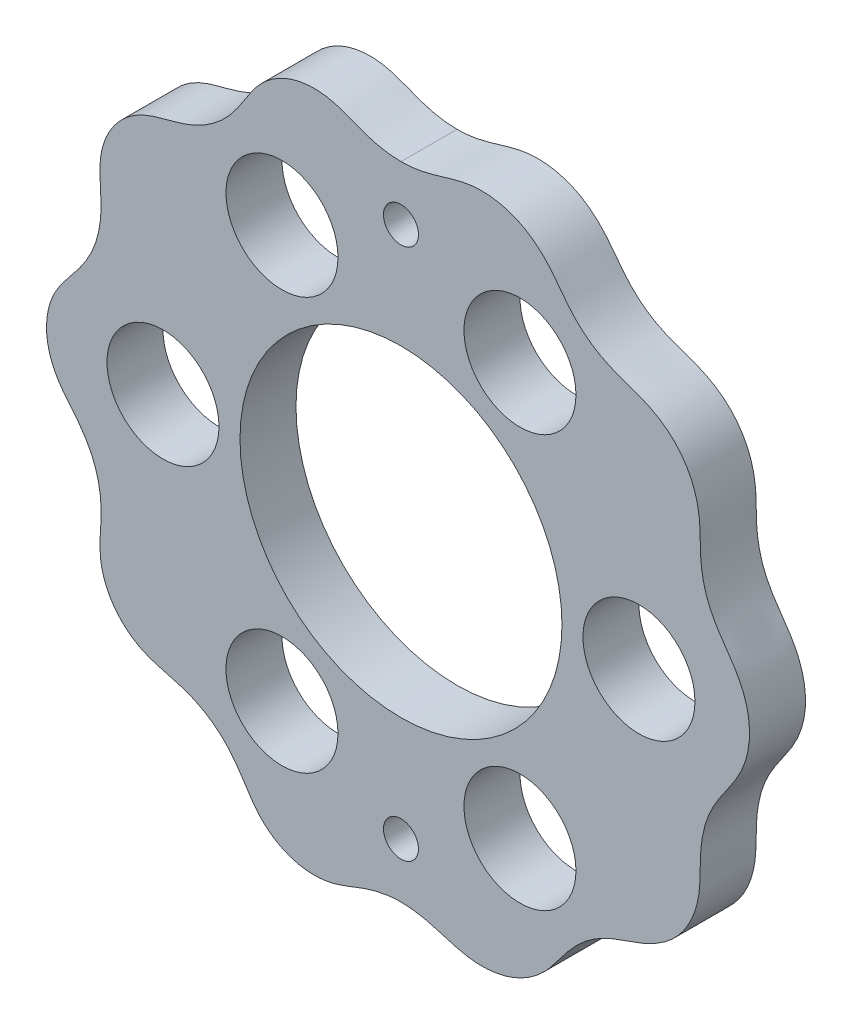
SolidWorks part; units mm, degrees
ref_plane "Front Plane" through (0, 0, 0) normal (1, 0, 0) x (0, 1, 0)
ref_plane "Top Plane" through (0, 0, 0) normal (0, 0, 1) x (0, 1, 0)
ref_plane "Right Plane" through (0, 0, 0) normal (0, 1, 0) x (-1, 0, 0)
sketch "Sketch1" plane through (0, 0, 0) normal (0, 0, 1) x (0, 1, 0)
  line L1 (23, 0) -> (-23, 0) construction
  spline S0 degree 4 poles (23.9407, 7.1162) (23.9885, 6.8946) (24.0625, 6.447) (24.1082, 5.7663) (24.0486, 4.9729) (23.9249, 4.3036) (23.7849, 3.7545) (23.6576, 3.3195) (23.5234, 2.8867) (23.3915, 2.4529) (23.27, 2.0165) (23.1655, 1.5748) (23.0935, 1.1854) (23.0516, 0.8757) (23.029, 0.6506) (23.0178, 0.5112) (23.0107, 0.398) (23.0053, 0.2791) (23.0017, 0.156) (22.9998, 0.0377) (22.9999, -0.0574) (23.0024, -0.1955) (23.0078, -0.3449) (23.0177, -0.5187) (23.0349, -0.7205) (23.0624, -0.9622) (23.1037, -1.2338) (23.154, -1.505) (23.2128, -1.774) (23.3284, -2.2422) (23.4854, -2.7704) (23.6744, -3.3607) (23.8702, -4.0673) (24.0032, -4.6933) (24.1066, -5.5543) (24.081, -6.4684) (23.913, -7.3677) (23.6084, -8.2271) (23.286, -8.8817) (22.8404, -9.5702) (22.2483, -10.2641) (21.497, -10.9281) (20.6148, -11.5684) (19.6504, -12.3151) (18.7036, -13.2841) (17.9844, -14.4202) (17.4982, -15.6468) (17.1396, -16.7614) (16.7678, -17.7216) (16.2174, -18.7181) (15.4262, -19.6865) (14.3018, -20.5828) (12.8167, -21.2533) (11.3354, -21.4856) (9.9796, -21.4697) (8.5912, -21.5223) (7.381, -21.7294) (6.1993, -22.1854) (5.0909, -22.8531) (4.209, -23.4942) (3.2301, -24.158) (2.0738, -24.7085) (0.7346, -25.0284) (-0.7346, -25.0284) (-2.0738, -24.7085) (-3.2301, -24.158) (-4.209, -23.4942) (-5.0909, -22.8531) (-6.1993, -22.1854) (-7.381, -21.7294) (-8.5912, -21.5223) (-9.9796, -21.4697) (-11.3354, -21.4856) (-12.8167, -21.2533) (-14.3018, -20.5828) (-15.4262, -19.6865) (-16.2174, -18.7181) (-16.7678, -17.7216) (-17.1396, -16.7614) (-17.4982, -15.6468) (-17.9844, -14.4202) (-18.7036, -13.2841) (-19.6504, -12.3151) (-20.6148, -11.5684) (-21.497, -10.9281) (-22.2483, -10.2641) (-22.8404, -9.5702) (-23.286, -8.8817) (-23.6084, -8.2271) (-23.913, -7.3677) (-24.081, -6.4684) (-24.1066, -5.5543) (-24.0032, -4.6933) (-23.8702, -4.0672) (-23.7111, -3.4935) (-23.5485, -2.9672) (-23.4068, -2.5063) (-23.2954, -2.1084) (-23.2128, -1.774) (-23.1541, -1.505) (-23.1037, -1.2338) (-23.0624, -0.9622) (-23.0349, -0.7205) (-23.0177, -0.5187) (-23.0078, -0.3449) (-23.0024, -0.1955) (-22.9999, -0.0574) (-22.9998, 0.0377) (-23.0017, 0.156) (-23.0053, 0.2791) (-23.0107, 0.398) (-23.0178, 0.5113) (-23.029, 0.6506) (-23.0459, 0.8192) (-23.0706, 1.0168) (-23.1141, 1.2964) (-23.1786, 1.6304) (-23.27, 2.0163) (-23.3915, 2.453) (-23.5234, 2.8866) (-23.6576, 3.3195) (-23.7849, 3.7545) (-23.9249, 4.3036) (-24.0486, 4.9729) (-24.1082, 5.7663) (-24.0625, 6.447) (-23.9885, 6.8946) (-23.9407, 7.1162) knots 0 0 0 0 0 0.009712 0.019424 0.029136 0.033992 0.038848 0.043704 0.04856 0.053416 0.058272 0.063128 0.067984 0.070412 0.071626 0.07284 0.074054 0.075268 0.076483 0.077697 0.079172 0.080648 0.082124 0.0836 0.086551 0.089503 0.092455 0.095406 0.098358 0.10131 0.113116 0.119019 0.124923 0.132722 0.14052 0.156118 0.163917 0.171717 0.179516 0.187315 0.198996 0.210676 0.222357 0.234038 0.251232 0.268425 0.279434 0.290443 0.301452 0.312461 0.328059 0.343658 0.362557 0.381456 0.391612 0.401768 0.42208 0.433761 0.445442 0.457123 0.468804 0.484402 0.5 0.515598 0.531196 0.542877 0.554558 0.566239 0.57792 0.598232 0.608388 0.618544 0.637443 0.656342 0.671941 0.687539 0.698548 0.709557 0.720566 0.731575 0.748768 0.765962 0.777643 0.789324 0.801004 0.812685 0.820484 0.828283 0.836083 0.843882 0.85948 0.867278 0.875077 0.880981 0.886884 0.892787 0.89869 0.901642 0.904594 0.907545 0.910497 0.913449 0.9164 0.917876 0.919352 0.920828 0.922303 0.923517 0.924732 0.925946 0.92716 0.928374 0.929588 0.932016 0.934444 0.936872 0.941728 0.946584 0.95144 0.956296 0.961152 0.966008 0.970864 0.980576 0.990288 1 1 1 1 1 construction
  spline S1 degree 4 poles (23, 0) (23, -0.0291) (23.0004, -0.0871) (23.0024, -0.1955) (23.0078, -0.3449) (23.0177, -0.5187) (23.0349, -0.7205) (23.0624, -0.9622) (23.1037, -1.2338) (23.154, -1.505) (23.2128, -1.774) (23.3284, -2.2422) (23.4854, -2.7704) (23.6744, -3.3607) (23.8702, -4.0673) (24.0032, -4.6933) (24.1066, -5.5543) (24.081, -6.4684) (23.913, -7.3677) (23.6084, -8.2271) (23.286, -8.8817) (22.8404, -9.5702) (22.2483, -10.2641) (21.497, -10.9281) (20.6148, -11.5684) (19.6504, -12.3151) (18.7036, -13.2841) (17.9844, -14.4202) (17.4982, -15.6468) (17.1396, -16.7614) (16.7678, -17.7216) (16.2174, -18.7181) (15.4262, -19.6865) (14.3018, -20.5828) (12.8167, -21.2533) (11.3354, -21.4856) (9.9796, -21.4697) (8.5912, -21.5223) (7.381, -21.7294) (6.1993, -22.1854) (5.0909, -22.8531) (4.209, -23.4942) (3.2301, -24.158) (2.0738, -24.7085) (0.7346, -25.0284) (-0.7346, -25.0284) (-2.0738, -24.7085) (-3.2301, -24.158) (-4.209, -23.4942) (-5.0909, -22.8531) (-6.1993, -22.1854) (-7.381, -21.7294) (-8.5912, -21.5223) (-9.9796, -21.4697) (-11.3354, -21.4856) (-12.8167, -21.2533) (-14.3018, -20.5828) (-15.4262, -19.6865) (-16.2174, -18.7181) (-16.7678, -17.7216) (-17.1396, -16.7614) (-17.4982, -15.6468) (-17.9844, -14.4202) (-18.7036, -13.2841) (-19.6504, -12.3151) (-20.6148, -11.5684) (-21.497, -10.9281) (-22.2483, -10.2641) (-22.8404, -9.5702) (-23.286, -8.8817) (-23.6084, -8.2271) (-23.913, -7.3677) (-24.081, -6.4684) (-24.1066, -5.5543) (-24.0032, -4.6933) (-23.8702, -4.0672) (-23.7111, -3.4935) (-23.5485, -2.9672) (-23.4068, -2.5063) (-23.2954, -2.1084) (-23.2128, -1.774) (-23.1541, -1.505) (-23.1037, -1.2338) (-23.0624, -0.9622) (-23.0349, -0.7205) (-23.0177, -0.5187) (-23.0078, -0.3449) (-23.0024, -0.1955) (-23.0004, -0.0871) (-23, -0.0291) (-23, 0) knots 0.077697 0.077697 0.077697 0.077697 0.077697 0.079172 0.080648 0.082124 0.0836 0.086551 0.089503 0.092455 0.095406 0.098358 0.10131 0.113116 0.119019 0.124923 0.132722 0.14052 0.156118 0.163917 0.171717 0.179516 0.187315 0.198996 0.210676 0.222357 0.234038 0.251232 0.268425 0.279434 0.290443 0.301452 0.312461 0.328059 0.343658 0.362557 0.381456 0.391612 0.401768 0.42208 0.433761 0.445442 0.457123 0.468804 0.484402 0.5 0.515598 0.531196 0.542877 0.554558 0.566239 0.57792 0.598232 0.608388 0.618544 0.637443 0.656342 0.671941 0.687539 0.698548 0.709557 0.720566 0.731575 0.748768 0.765962 0.777643 0.789324 0.801004 0.812685 0.820484 0.828283 0.836083 0.843882 0.85948 0.867278 0.875077 0.880981 0.886884 0.892787 0.89869 0.901642 0.904594 0.907545 0.910497 0.913449 0.9164 0.917876 0.919352 0.920828 0.922303 0.922303 0.922303 0.922303 0.922303
  spline S2 degree 4 poles (23, 0) (23, 0.1298) (23.0072, 0.4175) (23.0429, 0.8624) (23.1413, 1.4589) (23.2955, 2.0725) (23.4927, 2.6734) (23.7201, 3.2633) (23.9562, 3.8495) (24.1887, 4.4936) (24.3725, 5.2081) (24.4884, 6.2045) (24.367, 7.4987) (23.9005, 8.7389) (23.1142, 9.8103) (22.2077, 10.6059) (21.3141, 11.1767) (20.344, 11.7778) (19.3918, 12.5544) (18.5739, 13.4856) (17.9316, 14.559) (17.5362, 15.5855) (17.292, 16.5023) (17.061, 17.4211) (16.7439, 18.4274) (16.0925, 19.5887) (15.0517, 20.5947) (13.8291, 21.2551) (12.6398, 21.5687) (11.568, 21.6347) (10.5015, 21.5515) (9.4322, 21.4941) (8.3591, 21.5578) (7.3047, 21.7772) (6.2544, 22.1732) (5.2406, 22.7553) (4.2871, 23.5015) (3.3439, 24.3298) (2.1726, 25.0453) (0.7455, 25.4647) (-0.7455, 25.4647) (-2.1726, 25.0453) (-3.3439, 24.3298) (-4.2871, 23.5015) (-5.2406, 22.7553) (-6.2544, 22.1732) (-7.3047, 21.7772) (-8.3591, 21.5578) (-9.4322, 21.4941) (-10.5015, 21.5515) (-11.568, 21.6347) (-12.6398, 21.5687) (-13.8291, 21.2551) (-15.0517, 20.5947) (-16.0925, 19.5887) (-16.7439, 18.4274) (-17.061, 17.4211) (-17.292, 16.5023) (-17.5362, 15.5855) (-17.9316, 14.559) (-18.5739, 13.4856) (-19.3918, 12.5544) (-20.344, 11.7778) (-21.3141, 11.1767) (-22.2077, 10.6059) (-23.1142, 9.8103) (-23.9005, 8.7389) (-24.367, 7.4987) (-24.4884, 6.2045) (-24.3725, 5.2081) (-24.1887, 4.4936) (-23.9562, 3.8495) (-23.7201, 3.2633) (-23.4927, 2.6734) (-23.2955, 2.0725) (-23.1413, 1.4589) (-23.0429, 0.8624) (-23.0072, 0.4175) (-23, 0.1298) (-23, 0) knots 0.117046 0.117046 0.117046 0.117046 0.117046 0.121959 0.127941 0.133924 0.139906 0.145889 0.151871 0.157854 0.163836 0.171793 0.17975 0.195664 0.212603 0.221072 0.229542 0.24112 0.252698 0.264276 0.275854 0.287818 0.299782 0.305764 0.311746 0.32371 0.339624 0.355538 0.365648 0.375757 0.385867 0.395976 0.406129 0.416282 0.426435 0.436588 0.448463 0.460337 0.472211 0.484086 0.5 0.515914 0.527789 0.539663 0.551537 0.563412 0.573565 0.583718 0.593871 0.604024 0.614133 0.624243 0.634352 0.644462 0.660376 0.67629 0.688254 0.694236 0.700218 0.712182 0.724146 0.735724 0.747302 0.75888 0.770458 0.778928 0.787397 0.804336 0.82025 0.828207 0.836164 0.842146 0.848129 0.854111 0.860094 0.866076 0.872059 0.878041 0.882954 0.882954 0.882954 0.882954 0.882954
  spline S3 degree 1 poles (22.9, 0) (-22.9, 0) knots 0 0 1 1 construction
  spline S4 degree 1 poles (22.9, 0) (-22.9, 0) knots 0 0 1 1 construction
  spline S5 degree 3 poles (22.9, 0) (22.9, 0.8498) (23.2345, 2.558) (24.3571, 4.8421) (24.409, 7.3882) (23.4707, 9.299) (22.2655, 10.4476) (21.2067, 11.1223) (20.1347, 11.8109) (18.8343, 12.9292) (17.868, 14.3735) (17.3092, 15.9902) (17.0203, 17.2241) (16.6333, 18.4123) (15.7732, 19.8402) (14.4467, 20.9024) (12.8658, 21.4306) (11.6221, 21.5384) (10.3669, 21.4396) (8.6641, 21.3782) (6.9608, 21.7198) (5.437, 22.5115) (4.4077, 23.272) (3.4538, 24.101) (2.067, 25.0223) (0, 25.5202) (-2.067, 25.0223) (-3.4538, 24.101) (-4.4077, 23.272) (-5.437, 22.5115) (-6.9608, 21.7198) (-8.6641, 21.3782) (-10.3669, 21.4396) (-11.6221, 21.5384) (-12.8658, 21.4306) (-14.4467, 20.9024) (-15.7732, 19.8402) (-16.6333, 18.4123) (-17.0203, 17.2241) (-17.3092, 15.9902) (-17.868, 14.3735) (-18.8343, 12.9292) (-20.1347, 11.8109) (-21.2067, 11.1223) (-22.2655, 10.4476) (-23.4707, 9.299) (-24.409, 7.3882) (-24.3571, 4.8421) (-23.2345, 2.558) (-22.9, 0.8498) (-22.9, 0) knots 0.117046 0.117046 0.117046 0.117046 0.140981 0.164915 0.18885 0.212785 0.224752 0.236719 0.248686 0.260654 0.284588 0.296556 0.308523 0.32049 0.332458 0.356392 0.36836 0.380327 0.392294 0.404262 0.428196 0.440163 0.452131 0.464098 0.476065 0.5 0.523935 0.535902 0.547869 0.559837 0.571804 0.595738 0.607706 0.619673 0.63164 0.643608 0.667542 0.67951 0.691477 0.703444 0.715412 0.739346 0.751314 0.763281 0.775248 0.787215 0.81115 0.835085 0.859019 0.882954 0.882954 0.882954 0.882954
  spline S6 degree 3 poles (-22.9, 0) (-22.9, -0.0479) (-22.9011, -0.1371) (-22.9079, -0.3687) (-22.9315, -0.7258) (-23.0239, -1.452) (-23.3797, -2.8588) (-24.0593, -4.795) (-23.9714, -7.2665) (-23.1044, -9.1338) (-22.026, -10.3487) (-21.0767, -11.1162) (-20.0778, -11.8425) (-18.8298, -12.9452) (-17.6464, -14.7038) (-16.9913, -17.1042) (-15.8326, -19.2624) (-13.8798, -20.7982) (-11.5063, -21.4446) (-9.0354, -21.3117) (-6.9653, -21.724) (-5.4767, -22.4839) (-4.4548, -23.1876) (-3.455, -23.8966) (-2.0176, -24.6532) (0, -25.0645) (2.0176, -24.6532) (3.455, -23.8966) (4.4548, -23.1876) (5.4767, -22.4839) (6.9653, -21.724) (9.0354, -21.3117) (11.5063, -21.4446) (13.8798, -20.7982) (15.8326, -19.2624) (16.9913, -17.1042) (17.6464, -14.7038) (18.8298, -12.9452) (20.0778, -11.8425) (21.0767, -11.1162) (22.026, -10.3487) (23.1044, -9.1338) (23.9714, -7.2665) (24.0593, -4.795) (23.3797, -2.8588) (23.0239, -1.452) (22.9315, -0.7258) (22.9079, -0.3687) (22.9011, -0.1371) (22.9, -0.0479) (22.9, 0) knots 0.077697 0.077697 0.077697 0.077697 0.079346 0.080996 0.084295 0.090894 0.10409 0.130484 0.156878 0.183272 0.196469 0.209666 0.222863 0.23606 0.262454 0.288848 0.315242 0.341636 0.36803 0.394424 0.420818 0.434015 0.447212 0.460409 0.473606 0.5 0.526394 0.539591 0.552788 0.565985 0.579182 0.605576 0.63197 0.658364 0.684758 0.711152 0.737546 0.76394 0.777137 0.790334 0.803531 0.816728 0.843122 0.869516 0.89591 0.909106 0.915705 0.919004 0.920654 0.922303 0.922303 0.922303 0.922303
  dimension "D1" = 0.1
extrude "Boss-Extrude1" add sketch "Sketch1" along normal blind 4 contours S5 S6 | S1 S2
sketch "Sketch2" plane through (0, 0, 4) normal (0, 0, 1) x (1, 0, 0)
  circle A1 centre (17, 0) radius 4
  circle A2 centre (0, 0) radius 11.5
  circle A3 centre (8.5, -14.7224) radius 4
  circle A4 centre (-8.5, -14.7224) radius 4
  circle A5 centre (-17, 0) radius 4
  circle A6 centre (-8.5, 14.7224) radius 4
  circle A7 centre (8.5, 14.7224) radius 4
  point P19 (0, 0)
  dimension "D1" = 17
  dimension "D2" = 8
  dimension "D3" = 23
  dimension "D4" = 6
extrude "Cut-Extrude1" cut sketch "Sketch2" against normal through all contours A7 | A2 | A5 | A4 | A3 | A1 | A6
sketch "Sketch5" plane through (0, 0, 4) normal (0, 0, 1) x (1, 0, 0)
  line L0 (0, 0) -> (11.5, 0) construction
  circle A0 centre (0, 19) radius 1.25
  circle A1 centre (0, 0) radius 11.5 construction
  circle A2 centre (0, -19) radius 1.25
  dimension "D1" = 2.5
  dimension "D2" = 19
extrude "Cut-Extrude3" cut sketch "Sketch5" against normal through all contours A2 | A0
